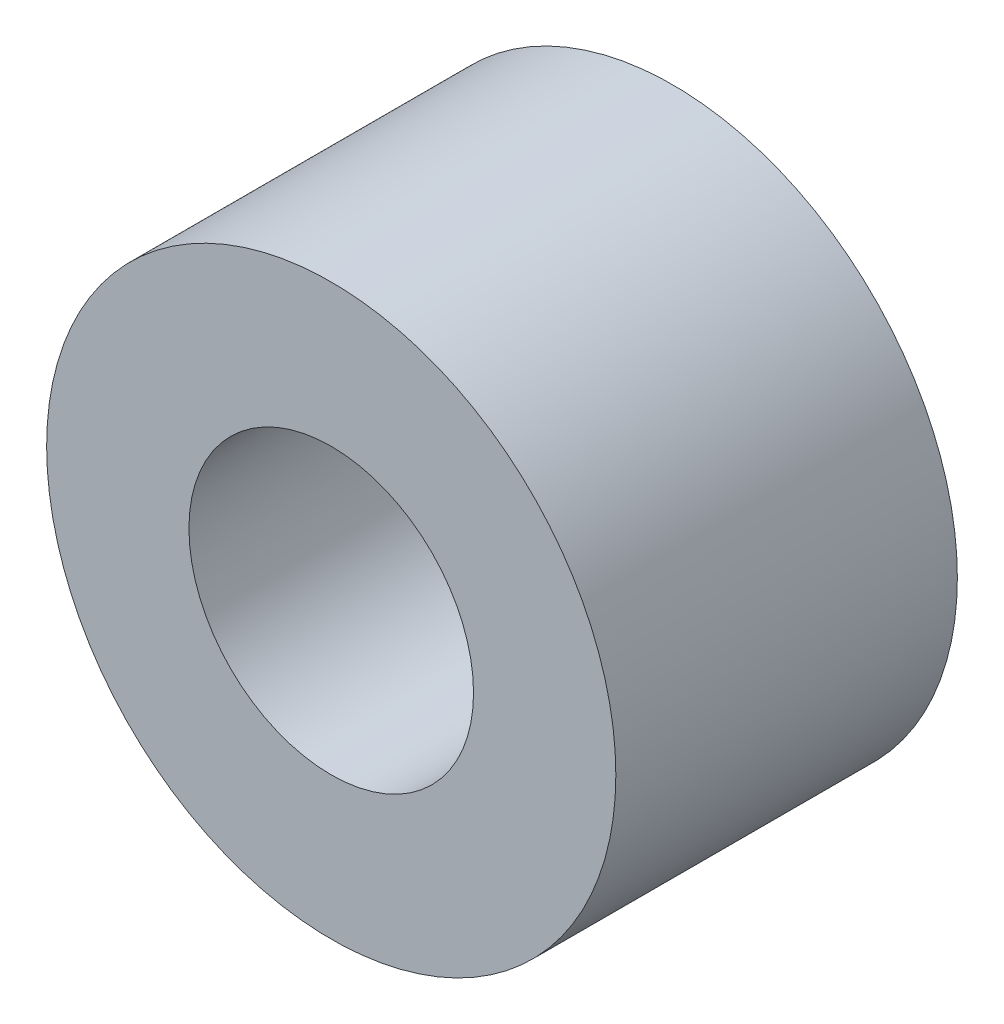
SolidWorks part; units mm, degrees
ref_plane "Alzado" through (0, 0, 0) normal (0, 0, 1) x (1, 0, 0)
ref_plane "Planta" through (0, 0, 0) normal (0, 1, 0) x (1, 0, 0)
ref_plane "Vista lateral" through (0, 0, 0) normal (1, 0, 0) x (0, 0, -1)
sketch "Croquis1" plane through (0, 0, 0) normal (0, 0, 1) x (1, 0, 0)
  circle A2 centre (45.5, 14.8) radius 2.5
  circle A3 centre (45.5, 14.8) radius 5
  dimension "D1" = 10
  dimension "D2" = 5
extrude "Saliente-Extruir1" add sketch "Croquis1" along normal blind 6
